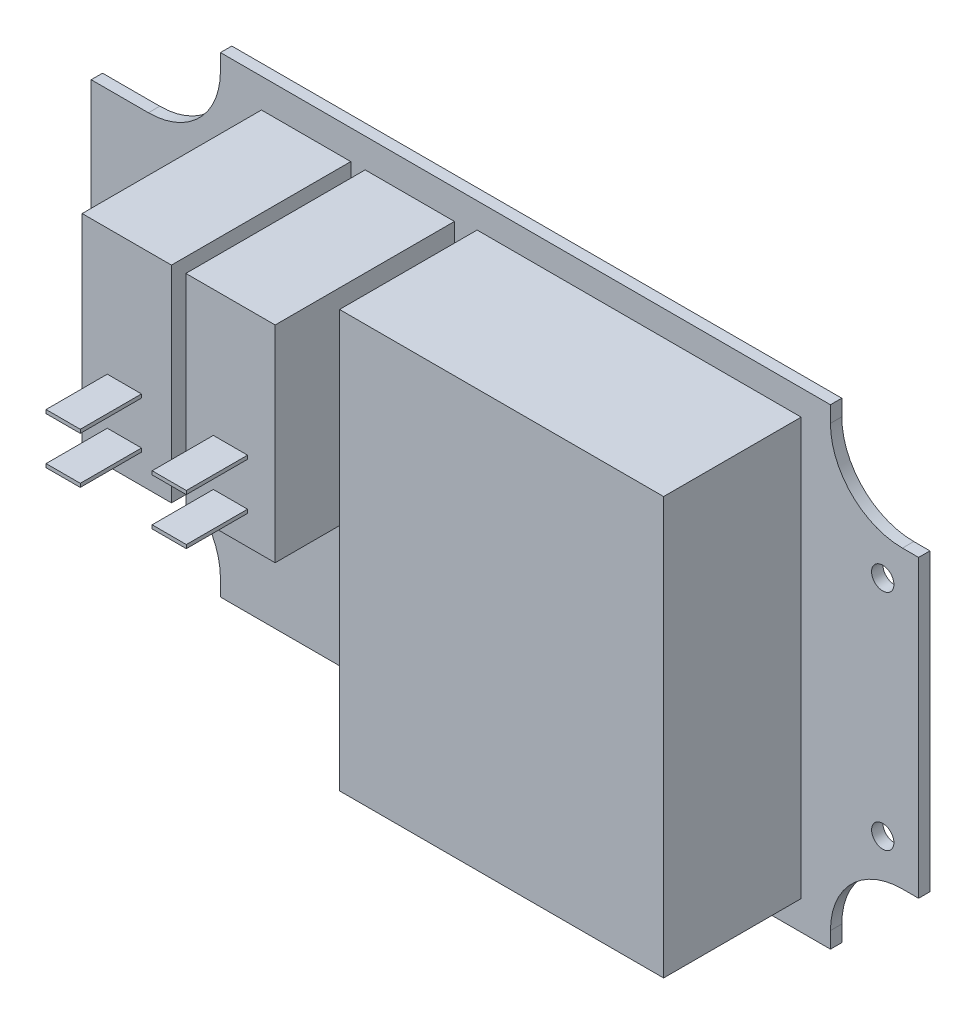
SolidWorks part; units mm, degrees
ref_plane "Front Plane" through (0, 0, 0) normal (0, 0, 1) x (1, 0, 0)
ref_plane "Top Plane" through (0, 0, 0) normal (0, 1, 0) x (1, 0, 0)
ref_plane "Right Plane" through (0, 0, 0) normal (1, 0, 0) x (0, 0, -1)
sketch "Sketch1" plane through (0, 0, 0) normal (0, 0, 1) x (1, 0, 0)
  line L0 (-42.3541, 30.2967) -> (-52.3541, 30.2967) construction
  line L1 (42.3541, -30.7033) -> (42.3541, -32.9433)
  line L2 (-52.3541, -20.7033) -> (-60.3013, -20.7033)
  line L4 (52.3541, -20.7033) -> (54.5933, -20.7033)
  line L5 (-52.3541, 30.2967) -> (-52.3541, 20.2967) construction
  line L6 (-52.3541, -20.7033) -> (-52.3541, -30.7033) construction
  line L7 (-52.3541, -30.7033) -> (-42.3541, -30.7033) construction
  line L8 (42.3541, -30.7033) -> (52.3541, -30.7033) construction
  line L9 (52.3541, -30.7033) -> (52.3541, -20.7033) construction
  line L10 (52.3541, 20.2967) -> (52.3541, 30.2967) construction
  line L11 (52.3541, 30.2967) -> (42.3541, 30.2967) construction
  line L12 (54.5933, -20.7033) -> (54.5933, 20.2967)
  line L13 (-60.3013, -20.7033) -> (-60.3013, 20.2967)
  line L14 (-60.3013, 20.2967) -> (-52.3541, 20.2967)
  line L15 (54.5933, 20.2967) -> (52.3541, 20.2967)
  line L16 (42.3541, -32.9433) -> (-42.3541, -32.9433)
  line L17 (-42.3541, -32.9433) -> (-42.3541, -30.7033)
  line L21 (0, -32.9433) -> (0, 0) construction
  line L24 (42.3541, 30.2967) -> (42.3541, 32.5367)
  line L25 (42.3541, 32.5367) -> (-42.3541, 32.5367)
  line L26 (-42.3541, 32.5367) -> (-42.3541, 30.2967)
  arc A0 (-42.3541, 30.2967) -> (-52.3541, 20.2967) centre (-52.3541, 30.2967) cw
  circle A1 centre (49.6183, -15.7283) radius 1.55
  arc A2 (-52.3541, -20.7033) -> (-42.3541, -30.7033) centre (-52.3541, -30.7033) cw
  circle A3 centre (49.6183, 15.3217) radius 1.55
  arc A4 (42.3541, 30.2967) -> (52.3541, 20.2967) centre (52.3541, 30.2967) ccw
  arc A5 (52.3541, -20.7033) -> (42.3541, -30.7033) centre (52.3541, -30.7033) ccw
  dimension "D1" = 41
  dimension "D2" = 3.1
  dimension "D3" = 10
  dimension "D4" = 4.975
  dimension "D5" = 84.7082
  dimension "D6" = 2.24
  dimension "D7" = 7.9472
  dimension "D8" = 2.2392
  dimension "D9" = 4.975
  dimension "D10" = 4.975
extrude "Boss-Extrude1" add sketch "Sketch1" along normal blind 1.5748
sketch "Sketch2" plane through (0, 0, 1.5748) normal (0, 0, 1) x (1, 0, 0)
  line L1 (-36.6572, 28.4742) -> (-24.2572, 28.4742)
  line L2 (-36.6572, 28.4742) -> (-36.6572, -0.1258)
  line L3 (-36.6572, -0.1258) -> (-24.2572, -0.1258)
  line L4 (-24.2572, 28.4742) -> (-24.2572, -0.1258)
  line L5 (-22.2572, 28.4742) -> (-9.8572, 28.4742)
  line L6 (-22.2572, 28.4742) -> (-22.2572, -0.1258)
  line L7 (-22.2572, -0.1258) -> (-9.8572, -0.1258)
  line L8 (-9.8572, 28.4742) -> (-9.8572, -0.1258)
  dimension "D1" = 2
  dimension "D2" = 28.6
  dimension "D3" = 12.4
extrude "Boss-Extrude2" add sketch "Sketch2" along normal blind 24.9
sketch "Sketch3" plane through (0, 0, 26.4748) normal (0, 0, 1) x (1, 0, 0)
  line L1 (-13.6892, 3.902) -> (-18.4392, 3.902)
  line L2 (-13.6892, 3.902) -> (-13.6892, 4.402)
  line L3 (-13.6892, 4.402) -> (-18.4392, 4.402)
  line L4 (-18.4392, 3.902) -> (-18.4392, 4.402)
  line L5 (-13.6892, 10.402) -> (-18.4392, 10.402)
  line L6 (-13.6892, 10.402) -> (-13.6892, 10.902)
  line L7 (-13.6892, 10.902) -> (-18.4392, 10.902)
  line L8 (-18.4392, 10.402) -> (-18.4392, 10.902)
  line L9 (-28.4177, 3.902) -> (-33.1677, 3.902)
  line L10 (-28.4177, 3.902) -> (-28.4177, 4.402)
  line L11 (-28.4177, 4.402) -> (-33.1677, 4.402)
  line L12 (-33.1677, 3.902) -> (-33.1677, 4.402)
  line L13 (-28.4177, 10.402) -> (-33.1677, 10.402)
  line L14 (-28.4177, 10.402) -> (-28.4177, 10.902)
  line L15 (-28.4177, 10.902) -> (-33.1677, 10.902)
  line L16 (-33.1677, 10.402) -> (-33.1677, 10.902)
  dimension "D1" = 0.5
  dimension "D2" = 4.75
  dimension "D3" = 6
extrude "Boss-Extrude3" add sketch "Sketch3" along normal blind 8.5
sketch "Sketch4" plane through (0, 0, 1.5748) normal (0, 0, 1) x (1, 0, 0)
  line L1 (38.2866, -28.8884) -> (-6.7134, -28.8884)
  line L2 (38.2866, -28.8884) -> (38.2866, 29.0116)
  line L3 (38.2866, 29.0116) -> (-6.7134, 29.0116)
  line L4 (-6.7134, -28.8884) -> (-6.7134, 29.0116)
  dimension "D1" = 57.9
  dimension "D2" = 45
extrude "Boss-Extrude4" add sketch "Sketch4" along normal blind 19.1
